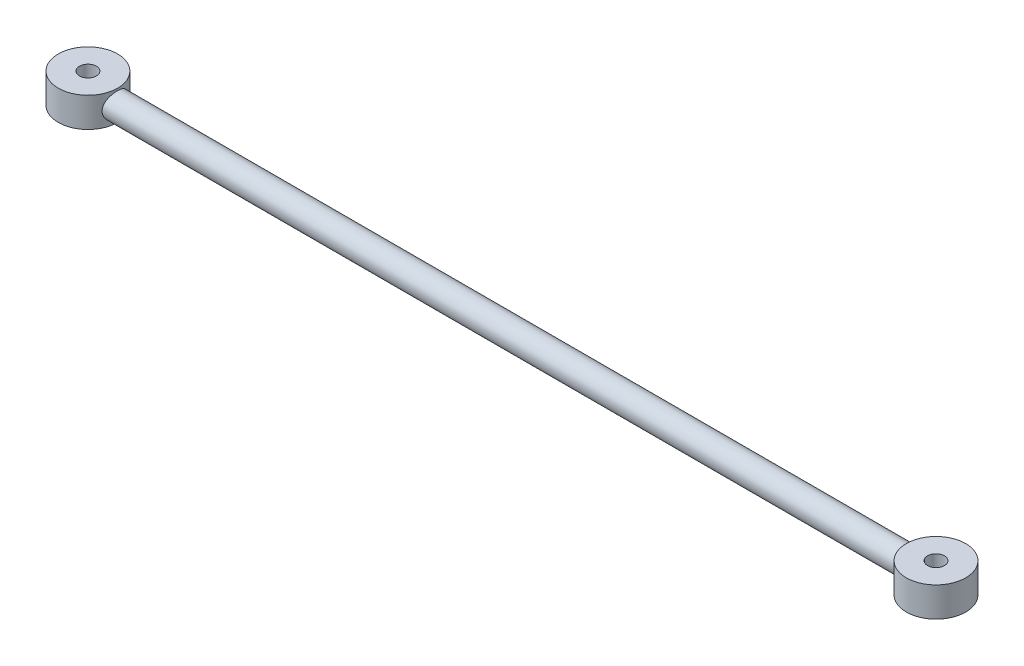
SolidWorks part; units mm, degrees
ref_plane "Front Plane" through (0, 0, 0) normal (0, 0, 1) x (1, 0, 0)
ref_plane "Top Plane" through (0, 0, 0) normal (0, 1, 0) x (1, 0, 0)
ref_plane "Right Plane" through (0, 0, 0) normal (1, 0, 0) x (0, 0, -1)
sketch "Sketch1" plane through (0, 0, 0) normal (0, 1, 0) x (1, 0, 0)
  line L0 (0, 0) -> (200, 0) construction
  circle A0 centre (0, 0) radius 7
  circle A1 centre (200, 0) radius 7
  circle A2 centre (0, 0) radius 2
  circle A3 centre (200, 0) radius 2
  dimension "D2" = 4
  dimension "D5" = 14
  dimension "D1" = 200
extrude "Boss-Extrude1" add sketch "Sketch1" along normal blind 7
ref_plane "Plane1" through (150, 0, 0) normal (1, 0, 0) x (0, 0, -1)
ref_plane "Plane2" through (22.5, 0, 0) normal (1, 0, 0) x (0, 0, -1)
sketch "Sketch2" plane through (22.5, 0, 0) normal (1, 0, 0) x (0, 0, -1)
  line L0 (0, 0) -> (0, 3.5) construction
  circle A0 centre (0, 3.5) radius 3
  dimension "D2" = 6
  dimension "D1" = 3.5
extrude "Boss-Extrude2" add sketch "Sketch2" along normal up to surface and the other way up to surface up to face at (200, 7, 7) other way up to face at (0, 7, 7)
